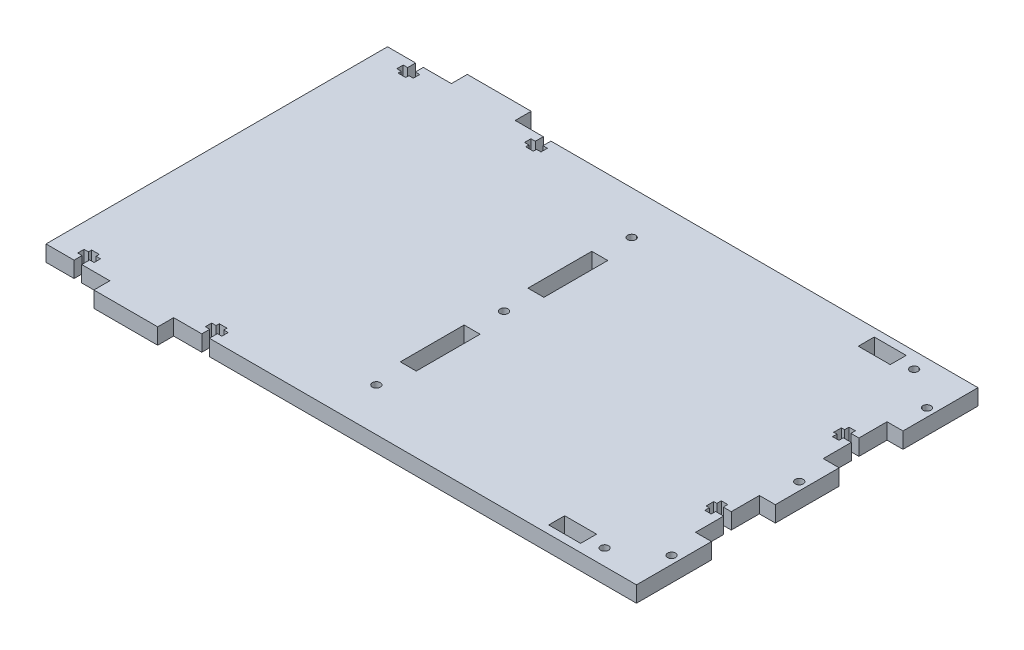
SolidWorks part; units mm, degrees
material "6061 Alloy"
ref_plane "Front Plane" through (0, 0, 0) normal (0, 0, 1) x (1, 0, 0)
ref_plane "Top Plane" through (0, 0, 0) normal (0, 1, 0) x (1, 0, 0)
ref_plane "Right Plane" through (0, 0, 0) normal (1, 0, 0) x (0, 0, -1)
sketch "Sketch1" plane through (0, 0, 0) normal (0, 1, 0) x (1, 0, 0)
  line L0 (-144.6071, 3.568) -> (-144.6071, -132.322)
  line L1 (-144.6071, -132.322) -> (-133.431, -132.322)
  line L2 (-130.3832, -132.322) -> (-119.2071, -132.322)
  line L3 (-93.8071, -132.322) -> (-82.631, -132.322)
  line L4 (-79.5832, -132.322) -> (-68.4071, -132.322)
  line L5 (-119.2071, -132.322) -> (-119.2071, -138.672)
  line L6 (-119.2071, -138.672) -> (-93.8071, -138.672)
  line L7 (-93.8071, -138.672) -> (-93.8071, -132.322)
  line L8 (-130.3832, -125.337) -> (-130.3832, -126.607)
  line L9 (-130.3832, -126.607) -> (-128.6306, -126.607)
  line L10 (-128.6306, -126.607) -> (-128.6306, -129.147)
  line L11 (-128.6306, -129.147) -> (-130.3832, -129.147)
  line L12 (-130.3832, -129.147) -> (-130.3832, -132.322)
  line L13 (-133.431, -125.337) -> (-133.431, -126.607)
  line L14 (-133.431, -126.607) -> (-135.1836, -126.607)
  line L15 (-135.1836, -126.607) -> (-135.1836, -129.147)
  line L16 (-135.1836, -129.147) -> (-133.431, -129.147)
  line L17 (-133.431, -129.147) -> (-133.431, -132.322)
  line L18 (-79.5832, -125.337) -> (-79.5832, -126.607)
  line L19 (-79.5832, -126.607) -> (-77.8306, -126.607)
  line L20 (-77.8306, -126.607) -> (-77.8306, -129.147)
  line L21 (-77.8306, -129.147) -> (-79.5832, -129.147)
  line L22 (-79.5832, -129.147) -> (-79.5832, -132.322)
  line L23 (-82.631, -125.337) -> (-82.631, -126.607)
  line L24 (-82.631, -126.607) -> (-84.3836, -126.607)
  line L25 (-84.3836, -126.607) -> (-84.3836, -129.147)
  line L26 (-84.3836, -129.147) -> (-82.631, -129.147)
  line L27 (-82.631, -129.147) -> (-82.631, -132.322)
  line L28 (-144.6071, 3.568) -> (-133.431, 3.568)
  line L29 (-130.3832, 3.568) -> (-119.2071, 3.568)
  line L30 (-93.8071, 3.568) -> (-82.631, 3.568)
  line L31 (-79.5832, 3.568) -> (-68.4071, 3.568)
  line L32 (-119.2071, 3.568) -> (-119.2071, 9.918)
  line L33 (-119.2071, 9.918) -> (-93.8071, 9.918)
  line L34 (-93.8071, 9.918) -> (-93.8071, 3.568)
  line L35 (-130.3832, -3.417) -> (-130.3832, -2.147)
  line L36 (-130.3832, -2.147) -> (-128.6306, -2.147)
  line L37 (-128.6306, -2.147) -> (-128.6306, 0.393)
  line L38 (-128.6306, 0.393) -> (-130.3832, 0.393)
  line L39 (-130.3832, 0.393) -> (-130.3832, 3.568)
  line L40 (-133.431, -3.417) -> (-133.431, -2.147)
  line L41 (-133.431, -2.147) -> (-135.1836, -2.147)
  line L42 (-135.1836, -2.147) -> (-135.1836, 0.393)
  line L43 (-135.1836, 0.393) -> (-133.431, 0.393)
  line L44 (-133.431, 0.393) -> (-133.431, 3.568)
  line L45 (-79.5832, -3.417) -> (-79.5832, -2.147)
  line L46 (-79.5832, -2.147) -> (-77.8306, -2.147)
  line L47 (-77.8306, -2.147) -> (-77.8306, 0.393)
  line L48 (-77.8306, 0.393) -> (-79.5832, 0.393)
  line L49 (-79.5832, 0.393) -> (-79.5832, 3.568)
  line L50 (-82.631, -3.417) -> (-82.631, -2.147)
  line L51 (-82.631, -2.147) -> (-84.3836, -2.147)
  line L52 (-84.3836, -2.147) -> (-84.3836, 0.393)
  line L53 (-84.3836, 0.393) -> (-82.631, 0.393)
  line L54 (-82.631, 0.393) -> (-82.631, 3.568)
  line L55 (-68.4071, 3.568) -> (83.9929, 3.568)
  line L56 (-68.4071, -132.322) -> (83.9929, -132.322)
  line L57 (-33.4821, -51.677) -> (-27.1321, -51.677)
  line L58 (-33.4821, -51.677) -> (-33.4821, -26.277)
  line L59 (-33.4821, -26.277) -> (-27.1321, -26.277)
  line L60 (-27.1321, -26.277) -> (-27.1321, -51.677)
  line L61 (-33.4821, -102.477) -> (-27.1321, -102.477)
  line L62 (-33.4821, -102.477) -> (-33.4821, -77.077)
  line L63 (-33.4821, -77.077) -> (-27.1321, -77.077)
  line L64 (-27.1321, -77.077) -> (-27.1321, -102.477)
  line L65 (83.9929, 3.568) -> (90.3429, 3.568)
  line L66 (83.9929, -132.322) -> (90.3429, -132.322)
  line L67 (83.9929, -51.677) -> (90.3429, -51.677)
  line L68 (83.9929, -51.677) -> (83.9929, -40.501)
  line L69 (83.9929, -26.277) -> (90.3429, -26.277)
  line L70 (83.9929, -102.477) -> (90.3429, -102.477)
  line L71 (83.9929, -102.477) -> (83.9929, -91.301)
  line L72 (83.9929, -77.077) -> (90.3429, -77.077)
  line L73 (90.3429, 3.568) -> (90.3429, -26.277)
  line L74 (90.3429, -51.677) -> (90.3429, -77.077)
  line L75 (90.3429, -102.477) -> (90.3429, -132.322)
  line L76 (77.0079, -40.501) -> (78.2779, -40.501)
  line L77 (78.2779, -40.501) -> (78.2779, -42.2536)
  line L78 (78.2779, -42.2536) -> (80.8179, -42.2536)
  line L79 (80.8179, -42.2536) -> (80.8179, -40.501)
  line L80 (80.8179, -40.501) -> (83.9929, -40.501)
  line L81 (77.0079, -37.4531) -> (78.2779, -37.4531)
  line L82 (78.2779, -37.4531) -> (78.2779, -35.7005)
  line L83 (78.2779, -35.7005) -> (80.8179, -35.7005)
  line L84 (80.8179, -35.7005) -> (80.8179, -37.4531)
  line L85 (80.8179, -37.4531) -> (83.9929, -37.4531)
  line L86 (77.0079, -91.301) -> (78.2779, -91.301)
  line L87 (78.2779, -91.301) -> (78.2779, -93.0536)
  line L88 (78.2779, -93.0536) -> (80.8179, -93.0536)
  line L89 (80.8179, -93.0536) -> (80.8179, -91.301)
  line L90 (80.8179, -91.301) -> (83.9929, -91.301)
  line L91 (77.0079, -88.2531) -> (78.2779, -88.2531)
  line L92 (78.2779, -88.2531) -> (78.2779, -86.5005)
  line L93 (78.2779, -86.5005) -> (80.8179, -86.5005)
  line L94 (80.8179, -86.5005) -> (80.8179, -88.2531)
  line L95 (80.8179, -88.2531) -> (83.9929, -88.2531)
  line L96 (58.5929, -5.957) -> (52.2429, -5.957)
  line L97 (52.2429, -5.957) -> (52.2429, 0.393)
  line L98 (52.2429, 0.393) -> (64.9429, 0.393)
  line L99 (64.9429, 0.393) -> (64.9429, -5.957)
  line L100 (64.9429, -5.957) -> (58.5929, -5.957)
  line L101 (58.5929, -122.797) -> (52.2429, -122.797)
  line L102 (52.2429, -122.797) -> (52.2429, -129.147)
  line L103 (52.2429, -129.147) -> (64.9429, -129.147)
  line L104 (64.9429, -129.147) -> (64.9429, -122.797)
  line L105 (64.9429, -122.797) -> (58.5929, -122.797)
  line L106 (-133.431, -3.417) -> (-130.3832, -3.417)
  line L107 (-82.631, -3.417) -> (-79.5832, -3.417)
  line L108 (-133.431, -125.337) -> (-130.3832, -125.337)
  line L109 (-82.631, -125.337) -> (-79.5832, -125.337)
  line L110 (77.0079, -37.4531) -> (77.0079, -40.501)
  line L111 (83.9929, -37.4531) -> (83.9929, -26.277)
  line L112 (83.9929, -88.2531) -> (83.9929, -77.077)
  line L113 (77.0079, -88.2531) -> (77.0079, -91.301)
  circle A0 centre (-30.3071, -13.577) radius 1.5875
  circle A1 centre (-30.3071, -64.377) radius 1.5875
  circle A2 centre (-30.3071, -115.177) radius 1.5875
  circle A3 centre (87.1679, -13.577) radius 1.5875
  circle A4 centre (87.1679, -64.377) radius 1.5875
  circle A5 centre (87.1679, -115.177) radius 1.5875
  circle A6 centre (71.2929, -2.782) radius 1.5875
  circle A7 centre (71.2929, -125.972) radius 1.5875
extrude "Boss-Extrude1" add sketch "Sketch1" along normal blind 6.35
